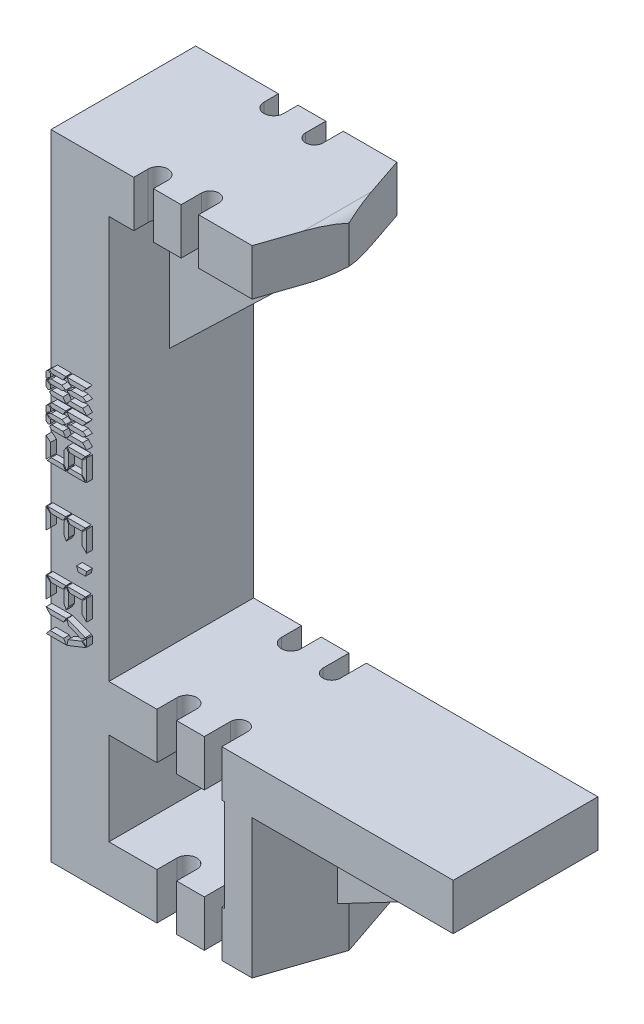
SolidWorks part; units mm, degrees
material "ABS"
ref_plane "Front" through (0, 0, 0) normal (0, 0, 1) x (1, 0, 0)
ref_plane "Top" through (0, 0, 0) normal (0, 1, 0) x (1, 0, 0)
ref_plane "Right" through (0, 0, 0) normal (1, 0, 0) x (0, 0, -1)
sketch "Sketch6" plane through (0, 0, 0) normal (0, 0, 1) x (1, 0, 0)
  line L0 (-25, 54.805) -> (15, 54.805)
  line L1 (15, 54.805) -> (15, 46.805)
  line L2 (15, 46.805) -> (-15, 46.805)
  line L3 (-15, 46.805) -> (-15, -46.805)
  line L4 (-15, -46.805) -> (25, -46.805)
  line L5 (25, -46.805) -> (25, -54.805)
  line L6 (25, -54.805) -> (-25, -54.805)
  line L7 (-25, -54.805) -> (-25, 54.805)
  line L8 (-25, 54.805) -> (25, -54.805) construction
  dimension "D1" = 109.61
  dimension "D2" = 8
  dimension "D4" = 50
  dimension "D5" = 40
extrude "Boss-Extrude2" add sketch "Sketch6" along normal mid plane 25
sketch "Sketch15" plane through (0, 0, 12.5) normal (0, 0, 1) x (1, 0, 0)
  line L0 (-15, -22.805) -> (15, -22.805)
  line L1 (-15, -46.805) -> (-15, 46.805) construction
  line L2 (-15, -30.805) -> (5, -30.805)
  line L3 (5, -54.805) -> (15, -54.805)
  line L4 (15, -54.805) -> (15, -22.805)
  line L5 (-25, -54.805) -> (25, -54.805) construction
  line L6 (-15, -30.805) -> (-15, -22.805)
  line L7 (5, -54.805) -> (5, -30.805)
  dimension "D2" = 8
extrude "Boss-Extrude3" add sketch "Sketch15" against normal up to surface (25 mm away) up to face at (0, 0, -12.5)
sketch "Sketch20" plane through (0, 54.805, 0) normal (0, 1, 0) x (1, 0, 0)
  line L0 (-10.7, 12.5) -> (-10.7, 10)
  line L1 (15, 12.5) -> (-25, 12.5) construction
  line L2 (-7.3, 10) -> (-7.3, 12.5)
  line L3 (-7.3, 12.5) -> (-10.7, 12.5)
  line L4 (0, 0) -> (15, 0) construction
  line L5 (15, -12.5) -> (15, 12.5) construction
  line L6 (-7.3, -12.5) -> (-10.7, -12.5)
  line L7 (-7.3, -10) -> (-7.3, -12.5)
  line L8 (-10.7, -12.5) -> (-10.7, -10)
  line L9 (-9, -10) -> (-9, 10) construction
  arc A0 (-10.7, 10) -> (-7.3, 10) centre (-9, 10) ccw
  arc A1 (-10.7, -10) -> (-7.3, -10) centre (-9, -10) cw
  dimension "D1" = 1.7
  dimension "D2" = 20
extrude "Cut-Extrude2" cut sketch "Sketch20" against normal up to next
sketch "Sketch21" plane through (0, -54.805, 0) normal (0, -1, 0) x (1, 0, 0)
  line L0 (-6.7, 12.5) -> (-6.7, 9)
  line L1 (-25, 12.5) -> (25, 12.5) construction
  line L2 (-3.3, 9) -> (-3.3, 12.5)
  line L3 (-3.3, 12.5) -> (-6.7, 12.5) construction
  line L4 (-5, -9) -> (-5, 9) construction
  line L5 (-6.7, 12.5) -> (-3.3, 12.5)
  line L7 (-3.3, -12.5) -> (-6.7, -12.5)
  line L8 (-3.3, -9) -> (-3.3, -12.5)
  line L9 (-6.7, -12.5) -> (-6.7, -9)
  arc A0 (-6.7, 9) -> (-3.3, 9) centre (-5, 9) ccw
  arc A1 (-6.7, -9) -> (-3.3, -9) centre (-5, -9) cw
  dimension "D1" = 1.7
  dimension "D2" = 18
extrude "Cut-Extrude3" cut sketch "Sketch21" against normal up to surface (32 mm away) up to face at (0, -22.805, 0)
sketch "Sketch22" plane through (0, 0, 0) normal (0, 0, 1) x (1, 0, 0)
  line L0 (-15, 21.805) -> (11, 46.805)
  line L1 (-7.3, 46.805) -> (15, 46.805) construction
  line L2 (-15, 46.805) -> (11, 46.805)
  line L5 (-15, -22.805) -> (-15, 46.805) construction
  line L7 (-15, 46.805) -> (-10.7, 46.805) construction
  line L8 (-15, 46.805) -> (-15, 21.805)
extrude "Boss-Extrude5" add sketch "Sketch22" along normal mid plane 4
fillet "Fillet7" radius 3 2 edges at (15, 54.805, 0) (15, 46.805, 0)
sketch "Sketch23" plane through (0, 54.805, 0) normal (0, 1, 0) x (1, 0, 0)
  line L0 (-2.51, 12.5) -> (-2.51, 9)
  line L1 (12, 12.5) -> (-7.3, 12.5) construction
  line L2 (0.51, 9) -> (0.51, 12.5)
  line L3 (0.51, 12.5) -> (-2.51, 12.5)
  line L4 (-9, 10) -> (-1, 10) construction
  line L5 (-1, 10) -> (-1, 9) construction
  line L6 (0, 0) -> (12, 0) construction
  line L7 (12, -12.5) -> (12, 12.5) construction
  line L8 (0.51, -12.5) -> (-2.51, -12.5)
  line L9 (0.51, -9) -> (0.51, -12.5)
  line L10 (-2.51, -12.5) -> (-2.51, -9)
  arc A0 (-2.51, 9) -> (0.51, 9) centre (-1, 9) ccw
  arc A1 (-2.51, -9) -> (0.51, -9) centre (-1, -9) cw
  dimension "D1" = 1.51
  dimension "D2" = 8
  dimension "D3" = 1
extrude "Cut-Extrude4" cut sketch "Sketch23" against normal up to next
sketch "Sketch24" plane through (0, -54.805, 0) normal (0, -1, 0) x (1, 0, 0)
  line L0 (1.49, -12.5) -> (1.49, -8)
  line L1 (-3.3, -12.5) -> (25, -12.5) construction
  line L2 (4.51, -8) -> (4.51, -12.5)
  line L3 (4.51, -12.5) -> (1.49, -12.5)
  line L4 (3, -8) -> (3, -9) construction
  line L5 (3, -9) -> (-5, -9) construction
  line L9 (4.51, 12.5) -> (1.49, 12.5)
  line L10 (4.51, 8) -> (4.51, 12.5)
  line L11 (1.49, 12.5) -> (1.49, 8)
  arc A0 (1.49, -8) -> (4.51, -8) centre (3, -8) cw
  arc A1 (1.49, 8) -> (4.51, 8) centre (3, 8) ccw
  dimension "D2" = 8
  dimension "D3" = 1
extrude "Cut-Extrude6" cut sketch "Sketch24" against normal up to surface (32 mm away) up to face at (-3.3333, -22.805, 0)
sketch "Sketch28" plane through (0, 54.805, 0) normal (0, 1, 0) x (1, 0, 0)
  line L0 (-10.7, 10) -> (-7.3, 10) construction
  line L1 (-10.7, -10) -> (-7.3, -10) construction
  line L2 (-7.3, -12.5) -> (-7.3, -10) construction
  arc A0 (-10.7, 10) -> (-7.3, 10) centre (-9, 10) ccw construction
  arc A1 (-7.3, -10) -> (-10.7, -10) centre (-9, -10) ccw construction
sketch "Sketch29" plane through (-25, 0, 0) normal (-1, 0, 0) x (0, 0, 1)
  line L0 (-12.5, 54.805) -> (12.5, 54.805)
  line L1 (12.5, 54.805) -> (12.5, -54.805)
  line L2 (12.5, -54.805) -> (-12.9424, -54.805)
  line L3 (-12.9424, -54.805) -> (-12.5, 54.805)
extrude "Cut-Extrude7" [suppressed] cut sketch "Sketch29" against normal blind 6
sketch "Sketch30" plane through (0, -46.805, 0) normal (0, 1, 0) x (1, 0, 0)
  line L0 (25, 12.5) -> (25, -12.5)
  line L1 (25, -12.5) -> (15, -12.5)
  line L2 (15, -12.5) -> (15, 12.5)
  line L3 (15, 12.5) -> (25, 12.5)
extrude "Cut-Extrude8" cut sketch "Sketch30" against normal up to surface (8 mm away) up to face at (-0.8, -54.805, 0)
sketch "Sketch34" plane through (0, -22.805, 0) normal (0, 1, 0) x (1, 0, 0)
  line L1 (9.755, 12.5) -> (14, 0)
  line L2 (15, -12.5) -> (4.51, -12.5) construction
  line L3 (9.755, -12.5) -> (15, -12.5)
  line L6 (15, 12.5) -> (9.755, 12.5)
  line L7 (15, 12.5) -> (4.51, 12.5) construction
  line L9 (15, -12.5) -> (15, 12.5)
  line L10 (15, 0) -> (14, 0) construction
  line L11 (14, 0) -> (9.755, -12.5)
extrude "Cut-Extrude9" cut sketch "Sketch34" against normal through all both and the other way through all
sketch "Sketch35" plane through (0, 0, 12.5) normal (0, 0, 1) x (1, 0, 0)
  line L0 (-17.85, 54.805) -> (-17.85, -54.805) construction
  line L1 (-10.7, 54.805) -> (-25, 54.805) construction
  line L2 (-25, -54.805) -> (-6.7, -54.805) construction
  text T0 "v3.3 6mm" font "Quartz" height 7
extrude "Boss-Extrude6" add sketch "Sketch35" along normal blind 1
sketch3d "3DSketch1"
  line L0 (4.51, -22.805, 12.5) -> (4.51, -30.805, 12.5)
  line L1 (4.51, -30.805, 12.5) -> (4.51, -30.805, -12.5)
  line L2 (4.51, -30.805, -12.5) -> (4.51, -22.805, -12.5)
  line L3 (4.51, -22.805, -12.5) -> (4.51, -22.805, 12.5)
extrude "Boss-Extrude7" add sketch "3DSketch1" along direction (1, 0, 0) on the side against the normal blind 40
sketch "Sketch37" plane through (0, 0, 0) normal (0, 0, 1) x (1, 0, 0)
  line L1 (14, -30.805) -> (44.51, -30.805)
  line L3 (5, -46.805) -> (14, -46.805) construction
  line L4 (14, -30.805) -> (14, -46.805)
  line L5 (14, -46.805) -> (44.51, -30.805)
extrude "Boss-Extrude17" add sketch "Sketch37" along direction (0, 0, 1) on the side of the normal mid plane 4 separate body
